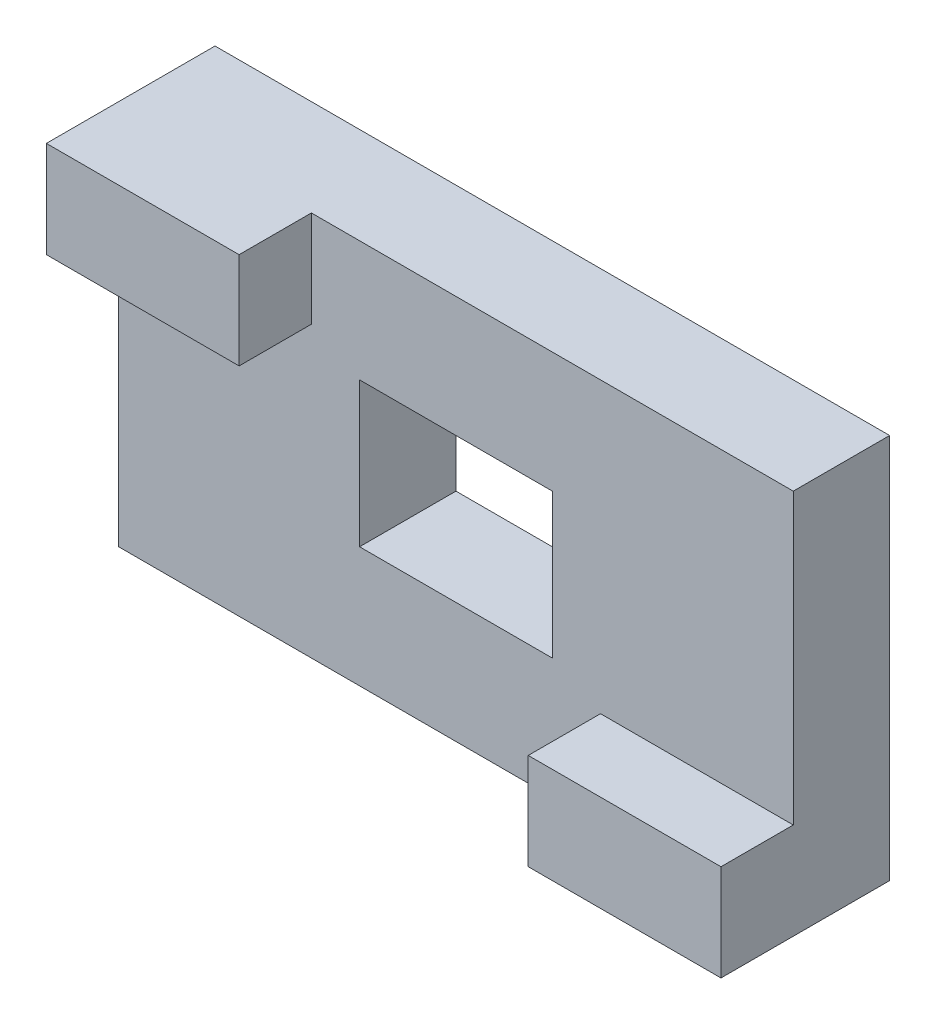
SolidWorks part; units mm, degrees
ref_plane "Front Plane" through (0, 0, 0) normal (0, 0, 1) x (1, 0, 0)
ref_plane "Top Plane" through (0, 0, 0) normal (0, 1, 0) x (1, 0, 0)
ref_plane "Right Plane" through (0, 0, 0) normal (1, 0, 0) x (0, 0, -1)
sketch "Sketch1" plane through (0, 0, 0) normal (0, 0, 1) x (1, 0, 0)
  line L1 (0, 0) -> (-56, 0)
  line L2 (0, 0) -> (0, 32)
  line L3 (0, 32) -> (-56, 32)
  line L4 (-56, 0) -> (-56, 32)
  line L5 (-36, 22) -> (-20, 22)
  line L6 (-36, 22) -> (-36, 10)
  line L7 (-36, 10) -> (-20, 10)
  line L8 (-20, 22) -> (-20, 10)
  dimension "D1" = 56
  dimension "D2" = 32
  dimension "D3" = 20
  dimension "D4" = 16
  dimension "D5" = 10
  dimension "D6" = 12
extrude "Boss-Extrude1" add sketch "Sketch1" along normal mid plane 8
sketch "Sketch2" plane through (0, 0, 4) normal (0, 0, 1) x (1, 0, 0)
  line L1 (-56, 32) -> (-40, 32)
  line L2 (-56, 32) -> (-56, 24)
  line L3 (-56, 24) -> (-40, 24)
  line L4 (-40, 32) -> (-40, 24)
  line L5 (0, 0) -> (-16, 0)
  line L6 (0, 0) -> (0, 8)
  line L7 (0, 8) -> (-16, 8)
  line L8 (-16, 0) -> (-16, 8)
  dimension "D1" = 16
  dimension "D2" = 8
  dimension "D3" = 16
  dimension "8" = 8
extrude "Boss-Extrude3" add sketch "Sketch2" along normal mid plane 12
